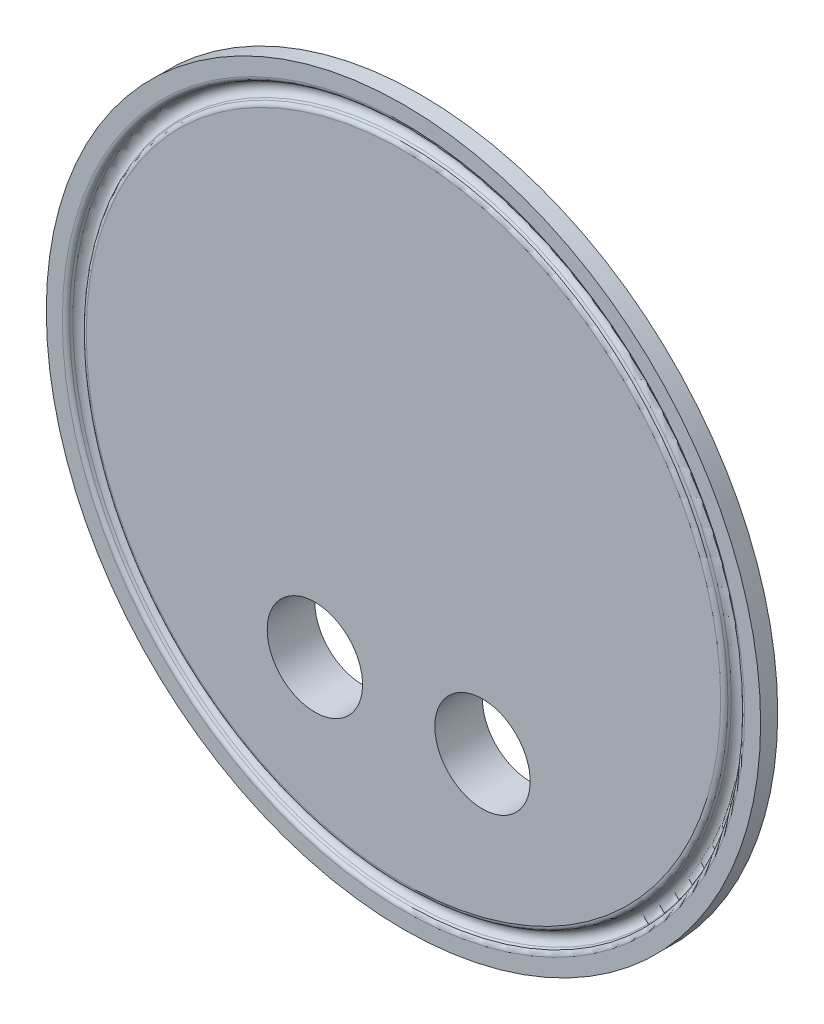
SolidWorks part; units mm, degrees
ref_plane "Front Plane" through (0, 0, 0) normal (0, 0, 1) x (1, 0, 0)
ref_plane "Top Plane" through (0, 0, 0) normal (0, 1, 0) x (1, 0, 0)
ref_plane "Right Plane" through (0, 0, 0) normal (1, 0, 0) x (0, 0, -1)
sketch "Sketch1" plane through (0, 0, 0) normal (1, 0, 0) x (0, 0, -1)
  line L0 (0, 0) -> (7.9248, 0) construction
  line L1 (0, 0) -> (0, 52.8099)
  line L2 (0, 59.4614) -> (2.8448, 59.4614)
  line L3 (2.8448, 59.4614) -> (7.9248, 45.5042)
  line L4 (7.9248, 45.5042) -> (7.9248, 0)
  line L5 (0, 56.7911) -> (0, 59.4614)
  line L6 (0.4797, 56.0663) -> (0.8729, 55.8994)
  line L7 (0.4797, 53.5347) -> (0.8729, 53.7016)
  line L8 (0, 56.2699) -> (0, 53.3311) construction
  line L9 (0, 54.8005) -> (0.4064, 54.8005) construction
  line L10 (0, 0) -> (7.9248, 0)
  arc A0 (0.8729, 53.7016) -> (0.8729, 55.8994) centre (0.4064, 54.8005) ccw
  arc A2 (0, 52.8099) -> (0.4797, 53.5347) centre (0.7874, 52.8099) cw
  arc A3 (0, 56.7911) -> (0.4797, 56.0663) centre (0.7874, 56.7911) ccw
  dimension "K" = 1.1938
  dimension "L" = 0.7874
  dimension "I" = 20
  dimension "C" = 91.0084
  dimension "F" = 2.8448
  dimension "H" = 0.4064
  dimension "B" = 109.601
  dimension "A" = 118.9228
  dimension "M" = 46
  dimension "N" = 23
  dimension "Length" = 7.9248
revolve "Revolve1" add sketch "Sketch1" angle 360 about L0
sketch "Sketch2" plane through (0, 0, -7.9248) normal (0, 0, -1) x (-1, 0, 0)
  circle A12 centre (-13.159, -27.5863) radius 7.9375
  circle A14 centre (14.7444, -27.5863) radius 7.9375
  circle A15 centre (-13.159, -27.5863) radius 13.716 construction
  circle A16 centre (14.7444, -27.5863) radius 13.716 construction
  point P0 (-13.159, -27.5863)
  dimension "D1" = 15.875
  dimension "D3" = 15.875
  dimension "D2" = 27.432
  dimension "D8" = 27.432
extrude "Cut-Extrude1" cut sketch "Sketch2" against normal through all
equation "\"D3@Sketch2\"=\"D1@Sketch2\""
equation "\"D8@Sketch2\"=\"D2@Sketch2\""
